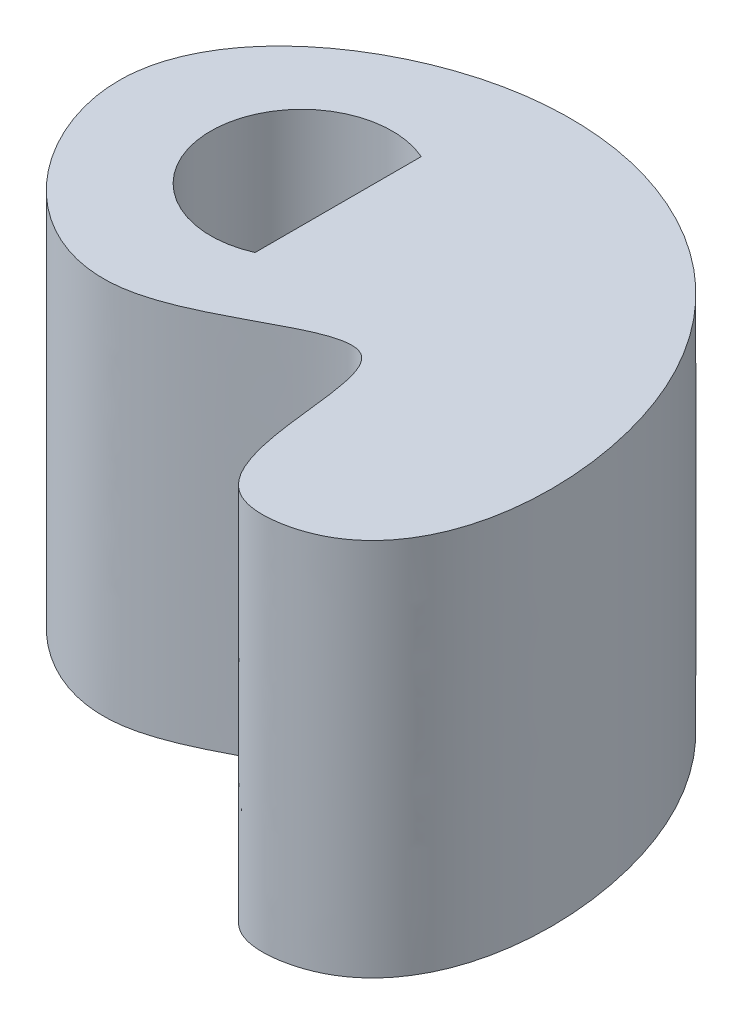
SolidWorks part; units mm, degrees
ref_plane "Front Plane" through (0, 0, 0) normal (0, 0, 1) x (1, 0, 0)
ref_plane "Top Plane" through (0, 0, 0) normal (0, 1, 0) x (1, 0, 0)
ref_plane "Right Plane" through (0, 0, 0) normal (1, 0, 0) x (0, 0, -1)
sketch "Sketch1" plane through (0, 0, 0) normal (0, 1, 0) x (1, 0, 0)
  line L0 (0.6092, 1.3817) -> (0.6092, -1.3817)
  arc A0 (0.6092, 1.3817) -> (0.6092, -1.3817) centre (0, 0) ccw
  spline S0 degree 3 poles (-0.5614, -4.5365) (-4.4337, 0.313) (0.7838, 4.3971) (6.9093, 1.5409) (6.6778, -4.954) (3.0264, -5.2346) (3.8309, -0.3014) (-0.5614, -4.5365) (-4.4337, 0.313) (0.7838, 4.3971) knots -0.382633 -0.268128 -0.153624 0 0.153624 0.396525 0.581158 0.617367 0.731872 0.846376 1 1.153624 1.396525 1.581158 only from (-3, 0) to (-3, 0)
extrude "Boss-Extrude1" add sketch "Sketch1" along normal blind 6.3
